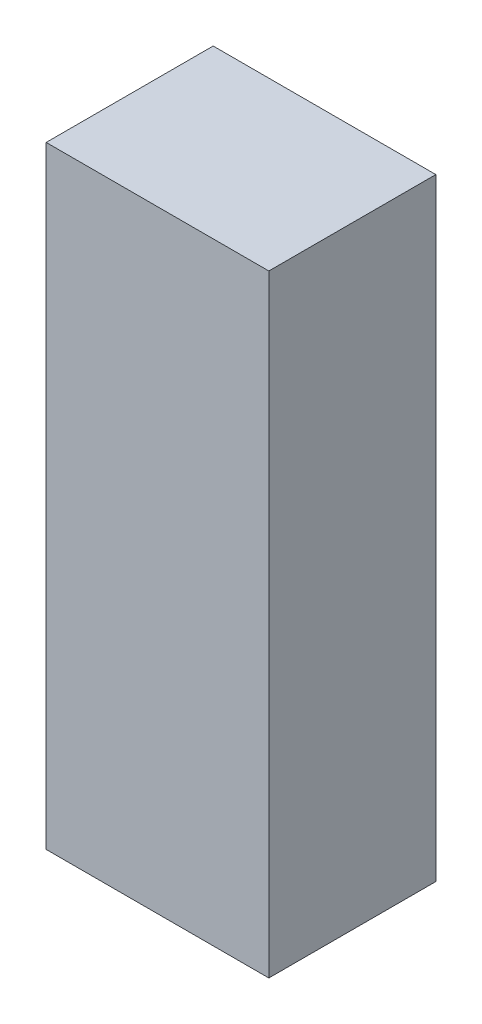
SolidWorks part; units mm, degrees
ref_plane "Front Plane" through (0, 0, 0) normal (0, 0, 1) x (1, 0, 0)
ref_plane "Top Plane" through (0, 0, 0) normal (0, 1, 0) x (1, 0, 0)
ref_plane "Right Plane" through (0, 0, 0) normal (1, 0, 0) x (0, 0, -1)
sketch "Sketch1" plane through (0, -3900, 0) normal (0, 1, 0) x (1, 0, 0)
  line L1 (0, 0) -> (-400, 0)
  line L2 (0, 0) -> (0, -300)
  line L3 (0, -300) -> (-400, -300)
  line L4 (-400, 0) -> (-400, -300)
  line L5 (0, 0) -> (-400, -300) construction
  line L6 (0, -300) -> (-400, 0) construction
  point P4 (-200, -150)
  dimension "D1" = 400
  dimension "D2" = 300
extrude "Boss-Extrude1" add sketch "Sketch1" along normal blind 1100
sketch "Sketch2" plane through (0, -3900, 0) normal (0, -1, 0) x (1, 0, 0)
  line L1 (-400, 300) -> (0, 300)
  line L2 (-400, 300) -> (-400, 0)
  line L3 (-400, 0) -> (0, 0)
  line L4 (0, 300) -> (0, 0)
  line L5 (-400, 300) -> (0, 0) construction
  line L6 (-400, 0) -> (0, 300) construction
  point P4 (-200, 150)
